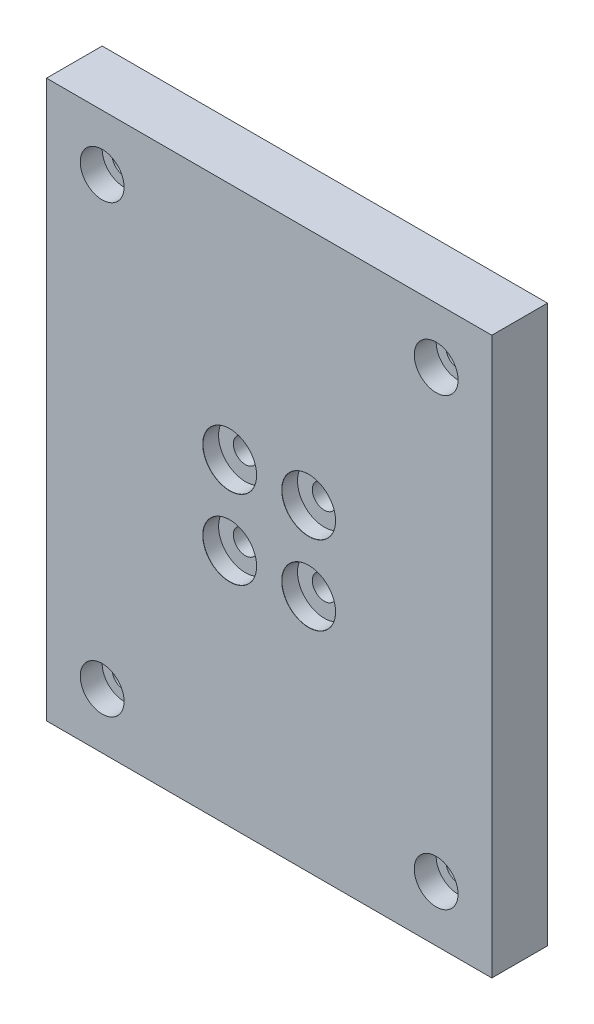
SolidWorks part; units mm, degrees
material "6061 Alloy"
ref_plane "Front" through (0, 0, 0) normal (0, 0, 1) x (1, 0, 0)
ref_plane "Top" through (0, 0, 0) normal (0, 1, 0) x (1, 0, 0)
ref_plane "Right" through (0, 0, 0) normal (1, 0, 0) x (0, 0, -1)
sketch "Sketch1" plane through (0, 0, 0) normal (0, 0, 1) x (1, 0, 0)
  line L1 (0, 0) -> (101.6, 0)
  line L2 (0, 0) -> (0, 127)
  line L3 (0, 127) -> (101.6, 127)
  line L4 (101.6, 0) -> (101.6, 127)
  dimension "D1" = 101.6
  dimension "D2" = 127
extrude "Boss-Extrude1" add sketch "Sketch1" along normal blind 12.7
sketch "Sketch5" plane through (0, 0, 12.7) normal (0, 0, 1) x (1, 0, 0)
  line L0 (50.8, 0) -> (50.8, 127) construction
  line L1 (0, 0) -> (101.6, 0) construction
  line L2 (101.6, 127) -> (0, 127) construction
  line L3 (-5.6233, 63.5) -> (108.9481, 63.5) construction
  line L4 (41.7957, 72.5) -> (59.8043, 54.5) construction
  line L5 (59.8043, 72.5) -> (41.7957, 54.5) construction
  circle A0 centre (41.7957, 54.5) radius 3.5299
  circle A1 centre (41.7957, 72.5) radius 3.2524
  circle A2 centre (59.8043, 72.5) radius 3.5727
  circle A3 centre (59.8043, 54.5) radius 3.3171
  point P18 (50.8, 63.5)
  point P19 (50.8, 63.5)
  dimension "D1" = 18
  dimension "D2" = 18.0086
  dimension "D3" = 63.5
hole_wizard "CBORE for M5 Hex Head Bolt1" positions "Sketch7" profile "Sketch8" counterbore size "M5" standard "ANSI Metric" end condition up to next
sketch "Sketch7" plane through (0, 0, 12.7) normal (0, 0, 1) x (1, 0, 0)
  point P0 (41.7957, 72.5)
  point P3 (59.8043, 72.5)
  point P6 (59.8043, 54.5)
  point P9 (41.7957, 54.5)
sketch "Sketch8" plane through (41.7957, 72.5, 12.7) normal (1, 0, 0) x (0, -1, 0)
  line L0 (0, 0) -> (0, 12.7)
  line L1 (0, 12.7) -> (2.75, 12.7)
  line L3 (2.75, 12.7) -> (2.75, 3.58)
  line L4 (6.12, 3.58) -> (2.75, 3.58)
  line L5 (6.12, 3.58) -> (6.12, 0.025)
  line L6 (6.12, 0.025) -> (6.145, 0)
  line L7 (6.145, 0) -> (0, 0)
  line L8 (-6.12, 0.025) -> (-6.145, 0) construction
  line L11 (0, -6.35) -> (0, 107.95) construction
  dimension "Thru Hole Dia." = 5.5
  dimension "Thru Hole Depth" = 12.7
  dimension "C'Bore Dia." = 12.24
  dimension "C'Bore Depth" = 3.58
  dimension "Near C'Sink Dia." = 12.29
  dimension "Near C'Sink Angle" = 90
hole_wizard "CBORE for M5 SHCS1" positions "Sketch10" profile "Sketch11" counterbore size "M5" standard "ANSI Metric" end condition through all
sketch "Sketch10" plane through (0, 0, 12.7) normal (0, 0, 1) x (1, 0, 0)
  line L0 (101.6, 127) -> (0, 127) construction
  line L1 (0, 127) -> (0, 0) construction
  line L2 (101.6, 0) -> (101.6, 127) construction
  line L3 (0, 0) -> (101.6, 0) construction
  point P0 (12.7, 114.3)
  point P2 (88.9, 114.3)
  point P4 (88.9, 12.7)
  point P6 (12.7, 12.7)
  dimension "D1" = 12.7
  dimension "D2" = 12.7
  dimension "D3" = 12.7
  dimension "D4" = 12.7
  dimension "D5" = 12.7
  dimension "D6" = 12.7
  dimension "D7" = 12.7
  dimension "D8" = 12.7
sketch "Sketch11" plane through (12.7, 114.3, 12.7) normal (1, 0, 0) x (0, -1, 0)
  line L0 (0, 0) -> (0, 12.7)
  line L1 (0, 12.7) -> (2.75, 12.7)
  line L3 (2.75, 12.7) -> (2.75, 5)
  line L4 (2.75, 5) -> (5, 5)
  line L5 (5, 5) -> (5, 0)
  line L7 (5, 0) -> (0, 0)
  line L11 (0, -6.35) -> (0, 107.95) construction
  dimension "Thru Hole Dia." = 5.5
  dimension "Thru Hole Depth" = 12.7
  dimension "C'Bore Dia." = 10
  dimension "C'Bore Depth" = 5
